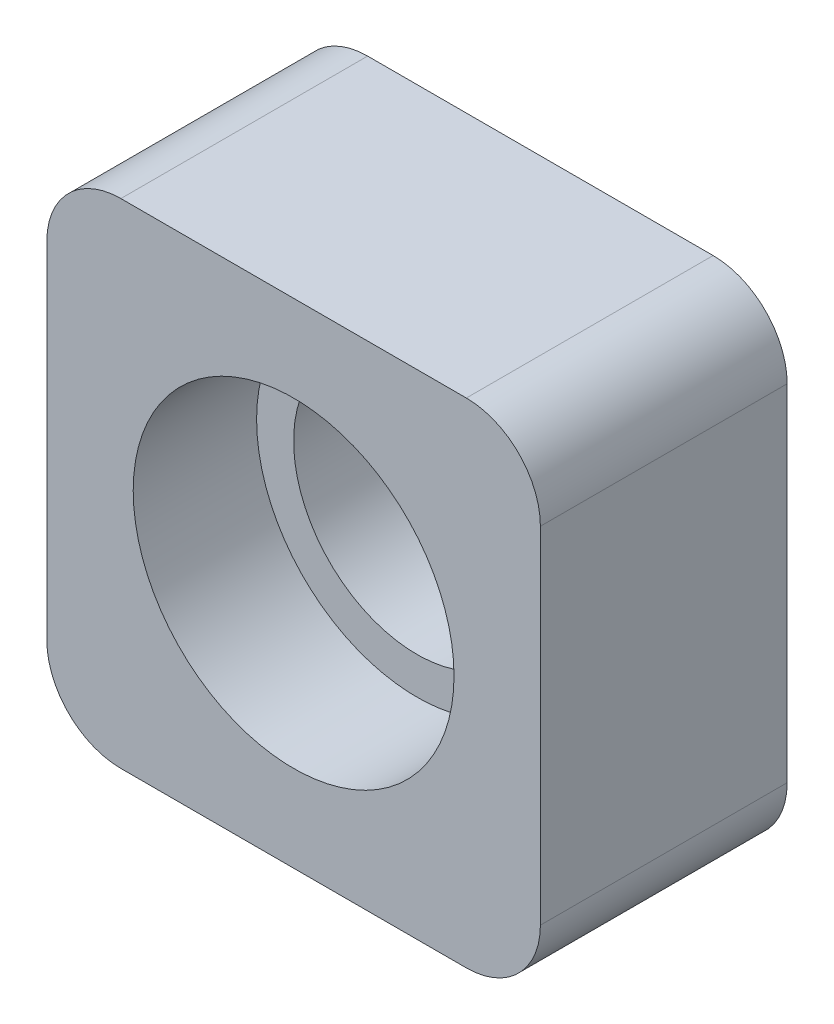
SolidWorks part; units mm, degrees
material "Plain Carbon Steel"
ref_plane "Front Plane" through (0, 0, 0) normal (0, 0, 1) x (1, 0, 0)
ref_plane "Top Plane" through (0, 0, 0) normal (0, 1, 0) x (1, 0, 0)
ref_plane "Right Plane" through (0, 0, 0) normal (1, 0, 0) x (0, 0, -1)
sketch "Sketch1" plane through (0, 0, 0) normal (0, 0, 1) x (1, 0, 0)
  line L1 (-10, -10) -> (10, -10)
  line L2 (-10, -10) -> (-10, 10)
  line L3 (-10, 10) -> (10, 10)
  line L4 (10, -10) -> (10, 10)
  line L5 (-10, -10) -> (10, 10) construction
  line L6 (-10, 10) -> (10, -10) construction
  point P0 (0, 0)
  dimension "D1" = 20
  dimension "D2" = 20
extrude "Boss-Extrude1" add sketch "Sketch1" along normal mid plane 10
fillet "Fillet1" radius 3 4 edges at (-10, -10, 0) (10, -10, 0) (-10, 10, 0) (10, 10, 0)
sketch "Sketch2" plane through (0, 0, 5) normal (0, 0, 1) x (1, 0, 0)
  circle A1 centre (0, 0) radius 5
  dimension "D1" = 10
extrude "Cut-Extrude1" cut sketch "Sketch2" against normal up to next
sketch "Sketch3" plane through (0, 0, 5) normal (0, 0, 1) x (1, 0, 0)
  circle A0 centre (0, 0) radius 6.5
  dimension "D1" = 13
extrude "Cut-Extrude2" cut sketch "Sketch3" against normal blind 5
